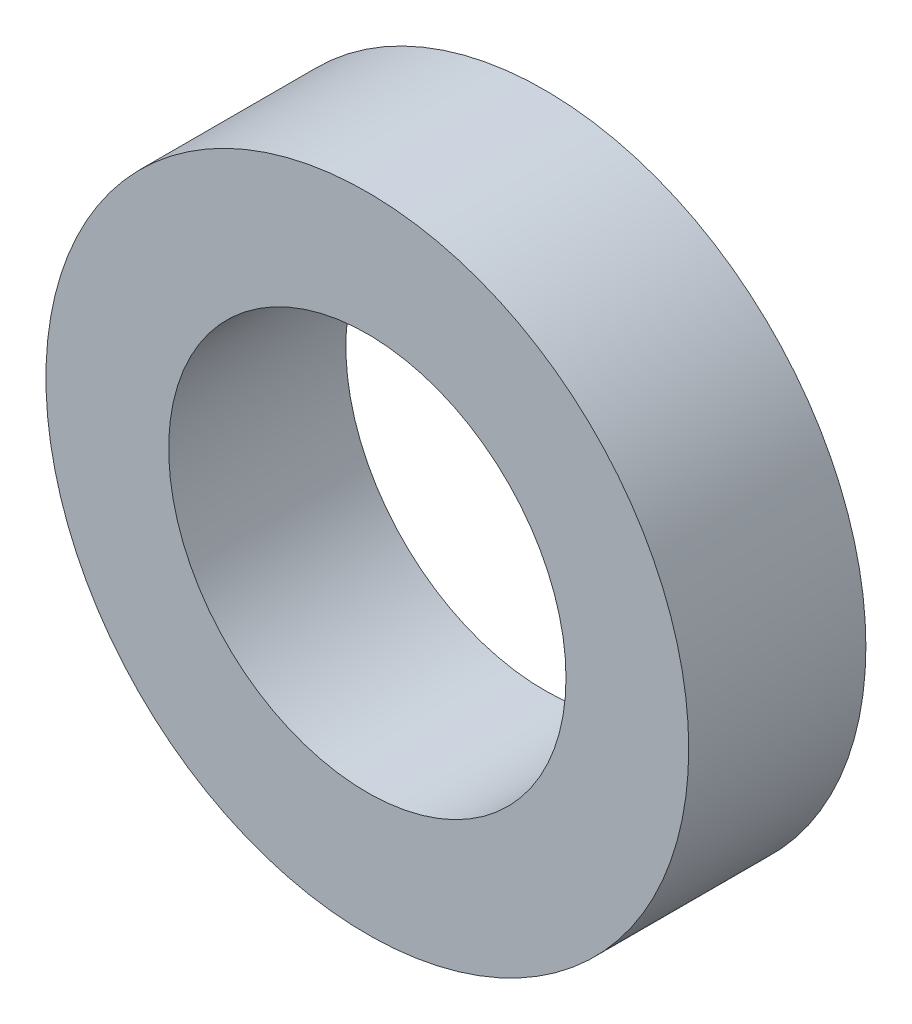
SolidWorks part; units mm, degrees
ref_plane "Спереди" through (0, 0, 0) normal (0, 0, 1) x (1, 0, 0)
ref_plane "Сверху" through (0, 0, 0) normal (0, 1, 0) x (1, 0, 0)
ref_plane "Справа" through (0, 0, 0) normal (1, 0, 0) x (0, 0, -1)
sketch "Эскиз1" plane through (0, 0, 0) normal (0, 0, 1) x (1, 0, 0)
  circle A0 centre (0, 0) radius 127
  circle A1 centre (0, 0) radius 78.5
extrude "Tire_reference" add sketch "Эскиз1" along normal blind 70 from offset 35
